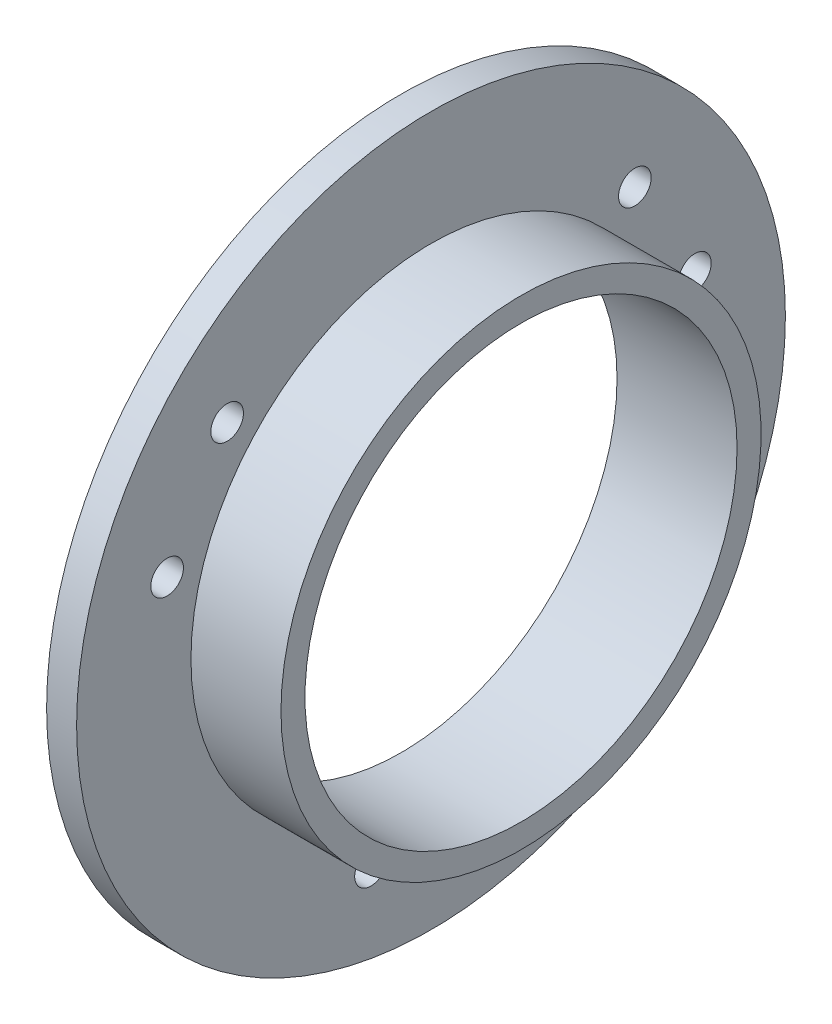
SolidWorks part; units mm, degrees
ref_plane "Front Plane" through (0, 0, 0) normal (0, 0, 1) x (1, 0, 0)
ref_plane "Top Plane" through (0, 0, 0) normal (0, 1, 0) x (1, 0, 0)
ref_plane "Right Plane" through (0, 0, 0) normal (1, 0, 0) x (0, 0, -1)
sketch "Sketch2" plane through (0, 0, 0) normal (1, 0, 0) x (0, 0, -1)
  circle A0 centre (0, 0) radius 37.5
  circle A7 centre (27.9217, 8.7882) radius 1.7272
  circle A8 centre (21.5717, 19.7868) radius 1.7272
  circle A9 centre (-21.5717, 19.7868) radius 1.7272
  circle A10 centre (-27.9217, 8.7882) radius 1.7272
  circle A11 centre (-6.35, -28.575) radius 1.7272
  circle A12 centre (6.35, -28.575) radius 1.7272
  circle A14 centre (0, 0) radius 22.86
  point P26 (0, 0)
  dimension "D1" = 75
  dimension "D2" = 3.4544
  dimension "D3" = 6.35
  dimension "D4" = 21.5717
  dimension "D5" = 27.9217
  dimension "D6" = 6.35
  dimension "D7" = 21.5717
  dimension "D8" = 27.9217
  dimension "D12" = 45.72
  dimension "D9" = 8.7882
  dimension "D10" = 19.7868
  dimension "D11" = 28.575
extrude "Boss-Extrude1" add sketch "Sketch2" along normal blind 3.175
sketch "Sketch3" plane through (3.175, 0, 0) normal (1, 0, 0) x (0, 0, -1)
  circle A0 centre (0, 0) radius 25.4
  circle A1 centre (0, 0) radius 22.86
  dimension "D1" = 50.8
  dimension "D2" = 45.72
extrude "Boss-Extrude2" add sketch "Sketch3" along normal blind 9.525
